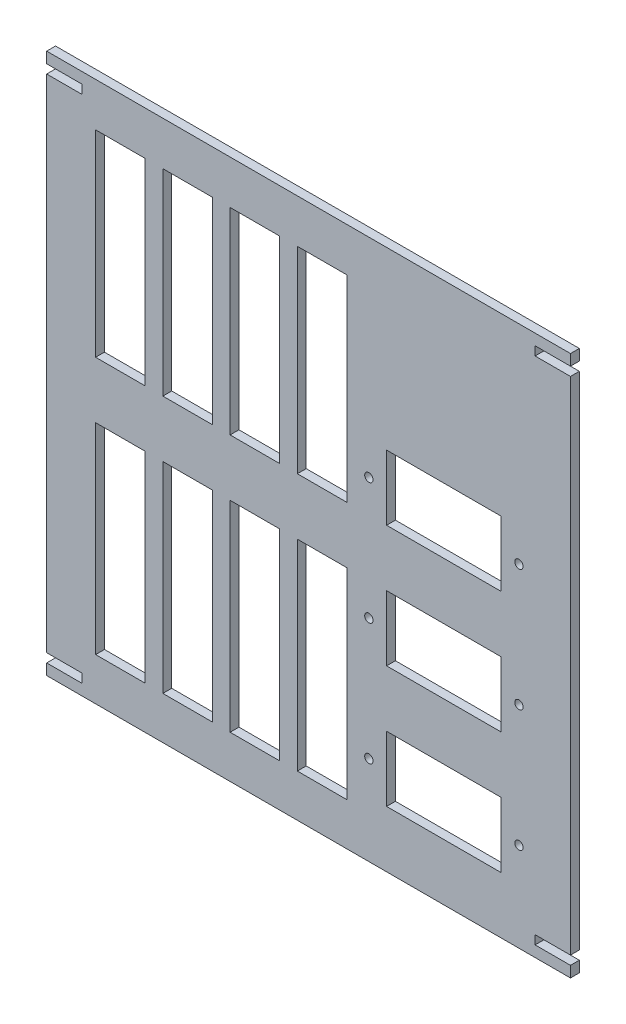
SolidWorks part; units mm, degrees
material "Delrin 2700 NC010, Low Viscosity Acetal Copolymer (SS)"
ref_plane "Front Plane" through (0, 0, 0) normal (0, 0, 1) x (1, 0, 0)
ref_plane "Top Plane" through (0, 0, 0) normal (0, 1, 0) x (1, 0, 0)
ref_plane "Right Plane" through (0, 0, 0) normal (1, 0, 0) x (0, 0, -1)
sketch "Sketch1" plane through (0, 0, 0) normal (0, 0, 1) x (1, 0, 0)
  line L0 (0, 48.514) -> (93.98, 48.514) construction
  line L1 (0, 0) -> (93.98, 0)
  line L2 (0, 0) -> (0, 1.9685)
  line L3 (0, 97.028) -> (93.98, 97.028)
  line L4 (93.98, 0) -> (93.98, 1.9685)
  line L5 (60.9826, 10.16) -> (81.5566, 10.16)
  line L6 (60.9826, 10.16) -> (60.9826, 21.844)
  line L7 (60.9826, 21.844) -> (81.5566, 21.844)
  line L8 (81.5566, 10.16) -> (81.5566, 21.844)
  line L9 (60.9826, 32.004) -> (81.5566, 32.004)
  line L10 (60.9826, 32.004) -> (60.9826, 43.688)
  line L11 (60.9826, 43.688) -> (81.5566, 43.688)
  line L12 (81.5566, 32.004) -> (81.5566, 43.688)
  line L13 (60.9826, 53.848) -> (81.5566, 53.848)
  line L14 (60.9826, 53.848) -> (60.9826, 65.532)
  line L15 (60.9826, 65.532) -> (81.5566, 65.532)
  line L16 (81.5566, 53.848) -> (81.5566, 65.532)
  line L17 (93.98, 95.0595) -> (87.63, 95.0595)
  line L18 (87.63, 95.0595) -> (87.63, 93.472)
  line L19 (87.63, 93.472) -> (93.98, 93.472)
  line L20 (93.98, 1.9685) -> (87.63, 1.9685)
  line L21 (87.63, 1.9685) -> (87.63, 3.556)
  line L22 (87.63, 3.556) -> (93.98, 3.556)
  line L23 (46.99, 0) -> (46.99, 43.688) construction
  line L24 (6.35, 1.9685) -> (6.35, 3.556)
  line L25 (0, 1.9685) -> (6.35, 1.9685)
  line L26 (6.35, 3.556) -> (0, 3.556)
  line L27 (0, 95.0595) -> (6.35, 95.0595)
  line L28 (6.35, 95.0595) -> (6.35, 93.472)
  line L29 (6.35, 93.472) -> (0, 93.472)
  line L30 (0, 3.556) -> (0, 93.472)
  line L31 (0, 95.0595) -> (0, 97.028)
  line L32 (93.98, 95.0595) -> (93.98, 97.028)
  line L33 (93.98, 3.556) -> (93.98, 93.472)
  line L34 (20.8455, 89.1895) -> (29.7355, 89.1895)
  line L35 (8.7805, 89.1895) -> (17.6705, 89.1895)
  line L36 (8.7805, 89.1895) -> (8.7805, 53.848)
  line L37 (8.7805, 7.6513) -> (17.6705, 7.6513)
  line L38 (17.6705, 89.1895) -> (17.6705, 53.848)
  line L39 (20.8455, 89.1895) -> (20.8455, 53.848)
  line L40 (20.8455, 7.6513) -> (29.7355, 7.6513)
  line L41 (29.7355, 89.1895) -> (29.7355, 53.848)
  line L42 (32.9105, 89.1895) -> (41.8005, 89.1895)
  line L43 (32.9105, 89.1895) -> (32.9105, 53.848)
  line L44 (32.9105, 7.6513) -> (41.8005, 7.6513)
  line L45 (41.8005, 89.1895) -> (41.8005, 53.848)
  line L46 (44.9755, 89.1895) -> (53.8655, 89.1895)
  line L47 (44.9755, 89.1895) -> (44.9755, 53.848)
  line L48 (44.9755, 7.6513) -> (53.8655, 7.6513)
  line L49 (53.8655, 89.1895) -> (53.8655, 53.848)
  line L50 (8.7805, 53.848) -> (17.6705, 53.848)
  line L51 (53.8655, 43.688) -> (44.9755, 43.688)
  line L52 (17.6705, 43.688) -> (17.6705, 7.6513)
  line L53 (8.7805, 43.688) -> (8.7805, 7.6513)
  line L54 (20.8455, 43.688) -> (20.8455, 7.6513)
  line L55 (29.7355, 43.688) -> (29.7355, 7.6513)
  line L56 (32.9105, 43.688) -> (32.9105, 7.6513)
  line L57 (41.8005, 43.688) -> (41.8005, 7.6513)
  line L58 (44.9755, 43.688) -> (44.9755, 7.6513)
  line L59 (46.99, 53.848) -> (46.99, 97.028) construction
  line L60 (53.8655, 43.688) -> (53.8655, 7.6513)
  line L61 (20.8455, 53.848) -> (29.7355, 53.848)
  line L62 (32.9105, 53.848) -> (41.8005, 53.848)
  line L63 (44.9755, 53.848) -> (53.8655, 53.848)
  line L64 (41.8005, 43.688) -> (32.9105, 43.688)
  line L65 (29.7355, 43.688) -> (20.8455, 43.688)
  line L66 (17.6705, 43.688) -> (8.7805, 43.688)
  circle A0 centre (57.8076, 16.002) radius 0.75
  circle A1 centre (84.7316, 16.002) radius 0.75
  circle A2 centre (57.8076, 37.846) radius 0.75
  circle A3 centre (84.7316, 37.846) radius 0.75
  circle A4 centre (57.8076, 59.69) radius 0.75
  circle A5 centre (84.7316, 59.69) radius 0.75
extrude "Boss-Extrude1" add sketch "Sketch1" along normal blind 1.5875
